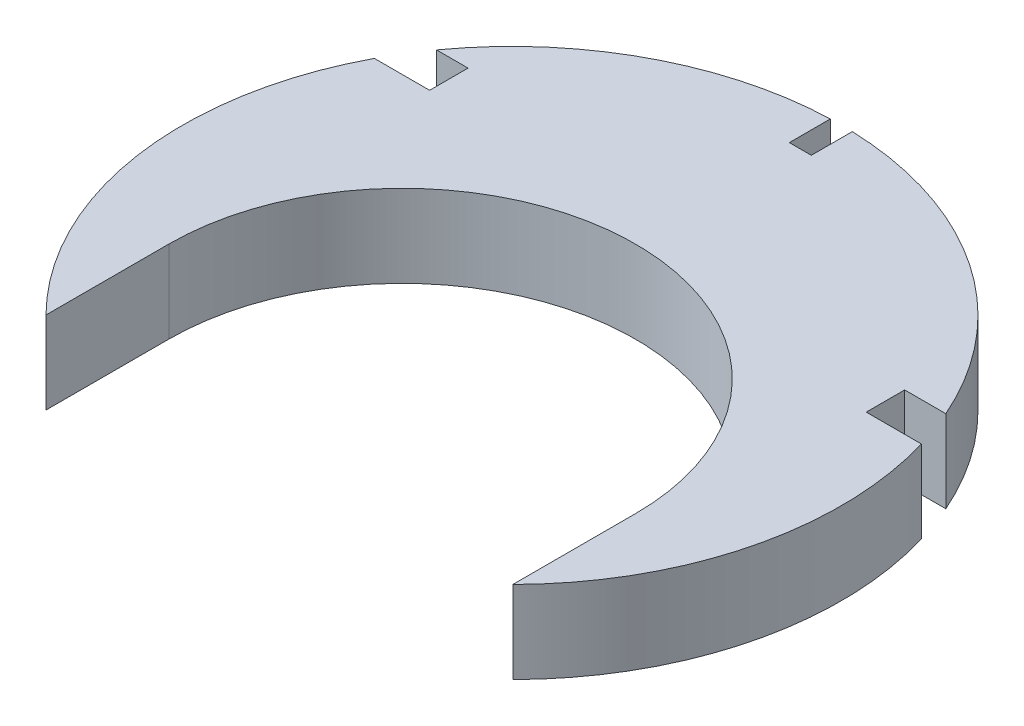
SolidWorks part; units mm, degrees
ref_plane "Front Plane" through (0, 0, 0) normal (0, 0, 1) x (1, 0, 0)
ref_plane "Top Plane" through (0, 0, 0) normal (0, 1, 0) x (1, 0, 0)
ref_plane "Right Plane" through (0, 0, 0) normal (1, 0, 0) x (0, 0, -1)
sketch "Sketch1" plane through (0, 3.6, 0) normal (0, 1, 0) x (1, 0, 0)
  line L0 (-8.6, 5.6) -> (-10.6132, 5.6)
  line L1 (-8.6, 5.6) -> (-11.1754, 5.6) construction
  line L2 (-10.6132, 5.6) -> (-8.6, 5.6)
  line L3 (-8.6, 7) -> (-8.6, 5.6)
  line L4 (-8.6, 7) -> (-9.7468, 7)
  line L5 (-0.4, 10.5) -> (-0.4, 11.9933)
  line L6 (-0.4, 10.5) -> (-0.4, 12.4936) construction
  line L7 (-0.4, 10.5) -> (0.4, 10.5)
  line L8 (0.4, 10.5) -> (0.4, 11.9933)
  line L9 (0.4, 10.5) -> (0.4, 12.4936) construction
  line L10 (11.5083, 3.4) -> (9.5, 3.4)
  line L11 (9.5, 3.4) -> (9.5, 4.8)
  line L12 (9.5, 4.8) -> (10.9982, 4.8)
  line L13 (11.5417, 4.8) -> (9.5, 4.8) construction
  line L14 (-8.5, -4) -> (-8.5, -9.1652)
  line L15 (8.5, -4) -> (8.5, -9.1652)
  arc A0 (-10.6132, 5.6) -> (11.5083, 3.4) centre (0, 0) ccw
  arc A1 (-0.4, 11.9933) -> (-9.7468, 7) centre (0, 0) ccw
  arc A2 (10.9982, 4.8) -> (0.4, 11.9933) centre (0, 0) ccw
  circle A3 centre (0, -4) radius 8.5
  circle A4 centre (0, 0) radius 12.5 construction
  line M2 (1, 10.5) -> (1, 12.4599)
  line M6 (0.4, 12.4936) -> (0.4, 10.5)
  line M7 (0.4, 10.5) -> (1, 10.5)
extrude "Boss-Extrude1" add sketch "Sketch1" along normal blind 3 contours A3 L15 A0 L10 L11 L12 A2 L7 L5 A1 L4 L3 L0 L14 M2 M7 | A2 M2 M6 M7
